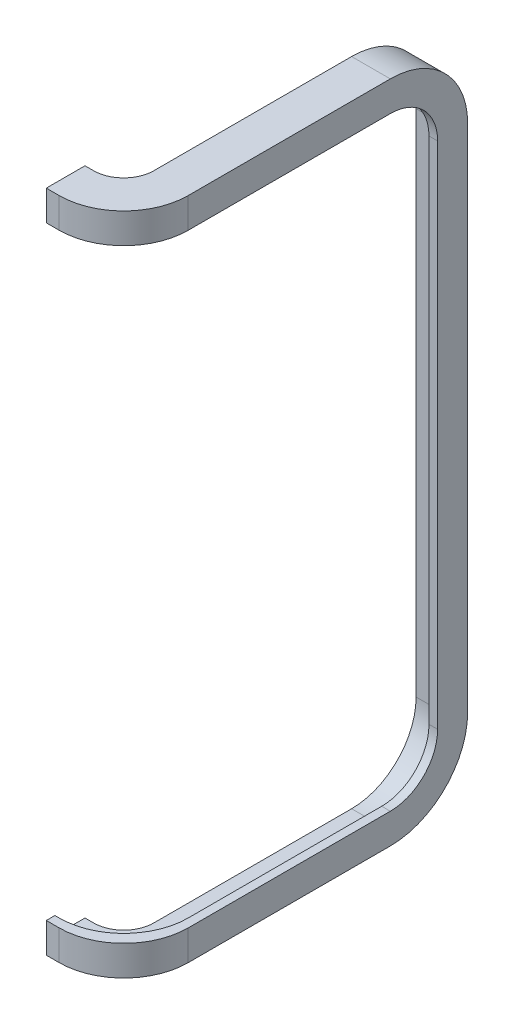
SolidWorks part; units mm, degrees
ref_plane "정면" through (0, 0, 0) normal (0, 0, 1) x (1, 0, 0)
ref_plane "윗면" through (0, 0, 0) normal (0, 1, 0) x (1, 0, 0)
ref_plane "우측면" through (0, 0, 0) normal (1, 0, 0) x (0, 0, -1)
ref_plane "평면1" through (105.5, 0, 0) normal (1, 0, 0) x (0, 0, -1)
sketch "스케치1" plane through (105.5, 0, 0) normal (1, 0, 0) x (0, 0, -1)
  line L0 (0, 0) -> (60, 0)
  line L1 (75, 15) -> (75, 133.5)
  line L2 (0, 0) -> (0, -3)
  line L3 (0, -3) -> (60, -3)
  line L4 (78, 15) -> (78, 133.5)
  line L5 (60, 151.5) -> (0, 151.5)
  line L6 (0, 151.5) -> (0, 148.5)
  line L7 (0, 148.5) -> (60, 148.5)
  line L8 (75, 15) -> (78, 15) construction
  line L9 (75, 133.5) -> (78, 133.5) construction
  line L10 (60, 151.5) -> (60, 148.5) construction
  arc A0 (60, 0) -> (75, 15) centre (60, 15) ccw
  arc A1 (75, 133.5) -> (60, 148.5) centre (60, 133.5) ccw
  arc A2 (60, -3) -> (78, 15) centre (60, 15) ccw
  arc A3 (78, 133.5) -> (60, 151.5) centre (60, 133.5) ccw
  point P15 (0, 133.9552)
  dimension "D2" = 15
  dimension "D1" = 60
  dimension "D3" = 3
  dimension "D4" = 148.5
extrude "보스-돌출1" add sketch "스케치1" along normal blind 7
sketch "스케치2" plane through (112.5, 0, 0) normal (1, 0, 0) x (0, 0, -1)
  line L0 (0, -3) -> (60, -3) construction
  line L1 (60, 151.5) -> (0, 151.5) construction
  line L2 (0, -3) -> (60, -3)
  line L3 (60, 151.5) -> (0, 151.5)
  line L4 (0, 151.5) -> (0, 144.5)
  line L8 (0, 4) -> (0, -3)
  line L11 (60, 4) -> (0, 4)
  line L12 (71, 133.5) -> (71, 15)
  line L13 (0, 144.5) -> (60, 144.5)
  line L14 (60, 4) -> (0, 4)
  line L15 (71, 133.5) -> (71, 15)
  line L16 (0, 144.5) -> (60, 144.5)
  arc A0 (60, -3) -> (78, 15) centre (60, 15) ccw construction
  arc A1 (78, 133.5) -> (60, 151.5) centre (60, 133.5) ccw construction
  arc A2 (60, -3) -> (78, 15) centre (60, 15) ccw
  arc A3 (78, 133.5) -> (60, 151.5) centre (60, 133.5) ccw
  arc A8 (60, 4) -> (71, 15) centre (60, 15) ccw
  arc A9 (71, 133.5) -> (60, 144.5) centre (60, 133.5) ccw
  arc A10 (60, 4) -> (71, 15) centre (60, 15) ccw
  arc A11 (71, 133.5) -> (60, 144.5) centre (60, 133.5) ccw
  point P0 (0, 144.5)
  point P3 (0, -3)
  point P11 (60, 4)
  point P12 (0, 144.5)
  point P15 (0, 4)
  point P16 (0, 4)
  line M9 (0, 0) -> (0, -3)
  line M10 (0, -3) -> (60, -3)
  arc M11 (60, -3) -> (78, 15) centre (60, 15) ccw
  line M12 (78, 15) -> (78, 133.5)
  arc M13 (78, 133.5) -> (60, 151.5) centre (60, 133.5) ccw
  line M14 (60, 151.5) -> (0, 151.5)
  line M15 (0, 151.5) -> (0, 148.5)
  line M16 (0, 148.5) -> (60, 148.5)
  arc M17 (60, 148.5) -> (75, 133.5) centre (60, 133.5) cw
  line M18 (75, 133.5) -> (75, 15)
  arc M19 (75, 15) -> (60, 0) centre (60, 15) cw
  line M20 (60, 0) -> (0, 0)
  dimension "D1" = 4
extrude "보스-돌출2" add sketch "스케치2" along normal blind 2 contours A11 L15 A10 L14 L8 L4 L16 M20 M19 M18 M17 M16 | M20 M9 M10 M11 M12 M13 M14 M15 M16 M17 M18 M19
sketch "스케치4" plane through (114.5, 0, 0) normal (1, 0, 0) x (0, 0, -1)
  line L0 (0, -3) -> (60, -3) construction
  line L1 (7, -3) -> (0, -3)
  line L2 (7, -3) -> (7, 0)
  line L3 (7, 0) -> (0, 0)
  line L4 (0, -3) -> (0, 0)
  line L5 (0, 148.5) -> (60, 148.5) construction
  line L6 (0, 151.5) -> (7, 151.5)
  line L7 (0, 151.5) -> (0, 148.5)
  line L8 (0, 148.5) -> (7, 148.5)
  line L9 (7, 151.5) -> (7, 148.5)
  dimension "D1" = 7
extrude "보스-돌출3" add sketch "스케치4" against normal blind 18
sketch "스케치5" plane through (114.5, 0, 0) normal (1, 0, 0) x (0, 0, -1)
  line L1 (0, 4) -> (-2, 4)
  line L2 (0, 4) -> (0, -3)
  line L3 (0, -3) -> (-2, -3)
  line L4 (-2, 4) -> (-2, -3)
  line L5 (0, 151.5) -> (-2, 151.5)
  line L6 (0, 151.5) -> (0, 144.5)
  line L7 (0, 144.5) -> (-2, 144.5)
  line L8 (-2, 151.5) -> (-2, 144.5)
  point P10 (0, 145.302)
  point P11 (0, 144.5)
  point P13 (0, -1.9901)
  point P14 (0, -3)
  dimension "D1" = 2
extrude "보스-돌출4" add sketch "스케치5" against normal blind 18
fillet "필렛1" radius 7 2 edges at (105.5, -1.5, -7) (105.5, 150, -7)
fillet "필렛2" radius 15 4 edges at (114.5, 0.5, 2) (112.5, 2, 0) (112.5, 146.5, 0) (114.5, 148, 2)
